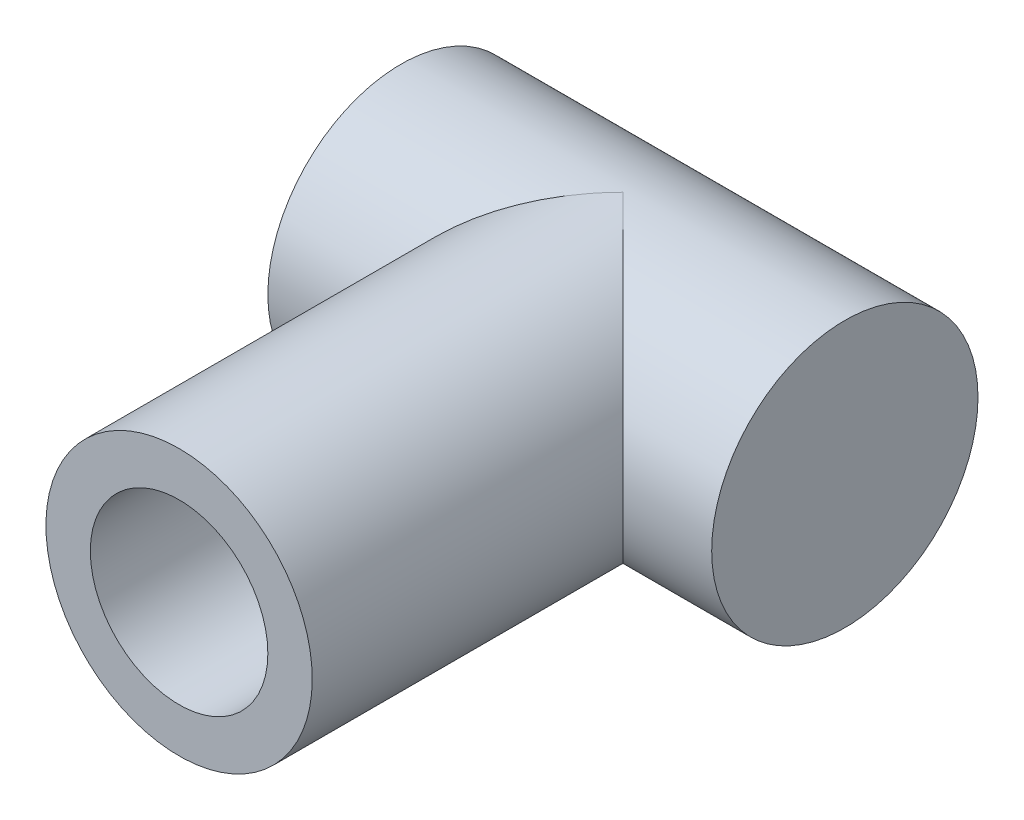
SolidWorks part; units mm, degrees
material "Plain Carbon Steel"
ref_plane "Front Plane" through (0, 0, 0) normal (0, 0, 1) x (1, 0, 0)
ref_plane "Top Plane" through (0, 0, 0) normal (0, 1, 0) x (1, 0, 0)
ref_plane "Right Plane" through (0, 0, 0) normal (1, 0, 0) x (0, 0, -1)
sketch "Sketch1" plane through (0, 0, 0) normal (1, 0, 0) x (0, 0, -1)
  circle A0 centre (0, 0) radius 75
  dimension "D1" = 150
extrude "Boss-Extrude1" add sketch "Sketch1" along normal mid plane 250
sketch "Sketch2" plane through (0, 0, 0) normal (0, 0, 1) x (1, 0, 0)
  circle A0 centre (0, 0) radius 75
  dimension "D1" = 150
extrude "Boss-Extrude2" add sketch "Sketch2" along normal blind 250
sketch "Sketch3" plane through (0, 0, 250) normal (0, 0, 1) x (1, 0, 0)
  circle A0 centre (0, 0) radius 50
  dimension "D1" = 100
extrude "Cut-Extrude1" cut sketch "Sketch3" against normal blind 150
